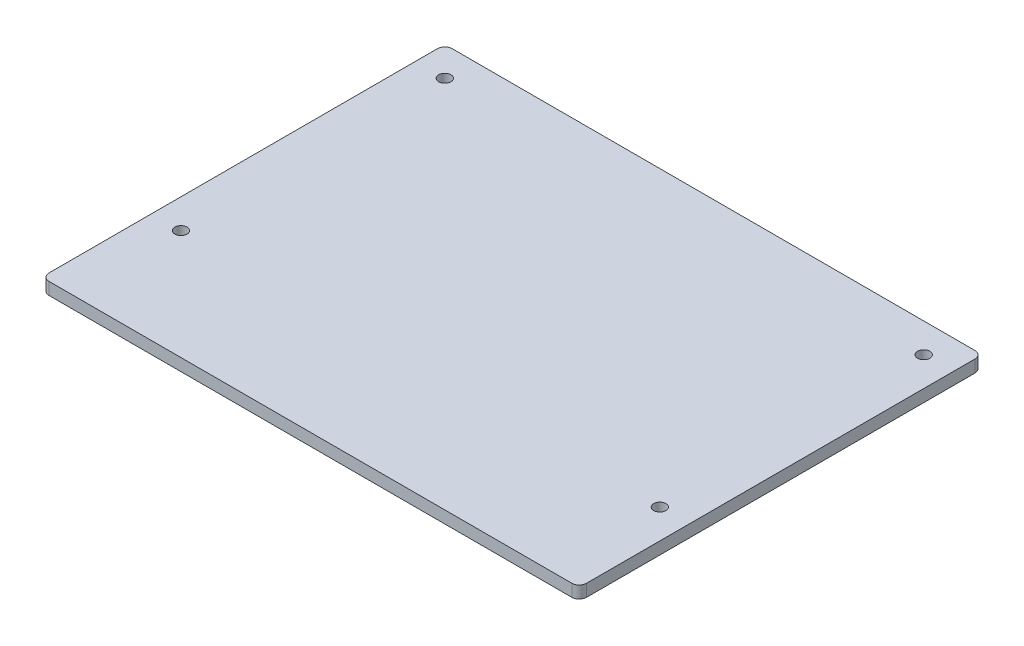
SolidWorks part; units mm, degrees
ref_plane "Front Plane" through (0, 0, 0) normal (0, 0, 1) x (1, 0, 0)
ref_plane "Top Plane" through (0, 0, 0) normal (0, 1, 0) x (1, 0, 0)
ref_plane "Right Plane" through (0, 0, 0) normal (1, 0, 0) x (0, 0, -1)
sketch "Sketch1" plane through (0, 0, 0) normal (0, 1, 0) x (1, 0, 0)
  line L0 (0, 82.5) -> (0, 159.1749) construction
  line L1 (-107, 82.5) -> (107, 82.5)
  line L2 (-110, 79.5) -> (-110, -79.5)
  line L3 (-107, -82.5) -> (107, -82.5)
  line L4 (110, 79.5) -> (110, -79.5)
  line L5 (-110, 82.5) -> (110, -82.5) construction
  line L6 (-110, -82.5) -> (110, 82.5) construction
  line L7 (-110, 0) -> (-37.2743, 0) construction
  arc A0 (-110, -79.5) -> (-107, -82.5) centre (-107, -79.5) ccw
  arc A1 (107, -82.5) -> (110, -79.5) centre (107, -79.5) ccw
  arc A2 (110, 79.5) -> (107, 82.5) centre (107, 79.5) ccw
  arc A3 (-110, 79.5) -> (-107, 82.5) centre (-107, 79.5) cw
  circle A4 centre (-98, -37.5) radius 2.5
  circle A5 centre (-98, 70.5) radius 2.5
  circle A6 centre (98, 70.5) radius 2.5
  circle A7 centre (98, -37.5) radius 2.5
  point P0 (0, 0)
  dimension "D1" = 3
  dimension "D2" = 12
  dimension "D3" = 45
  dimension "D4" = 12
  dimension "D5" = 12
  dimension "D6" = 12
  dimension "D7" = 12
extrude "Boss-Extrude1" add sketch "Sketch1" along normal blind 5
